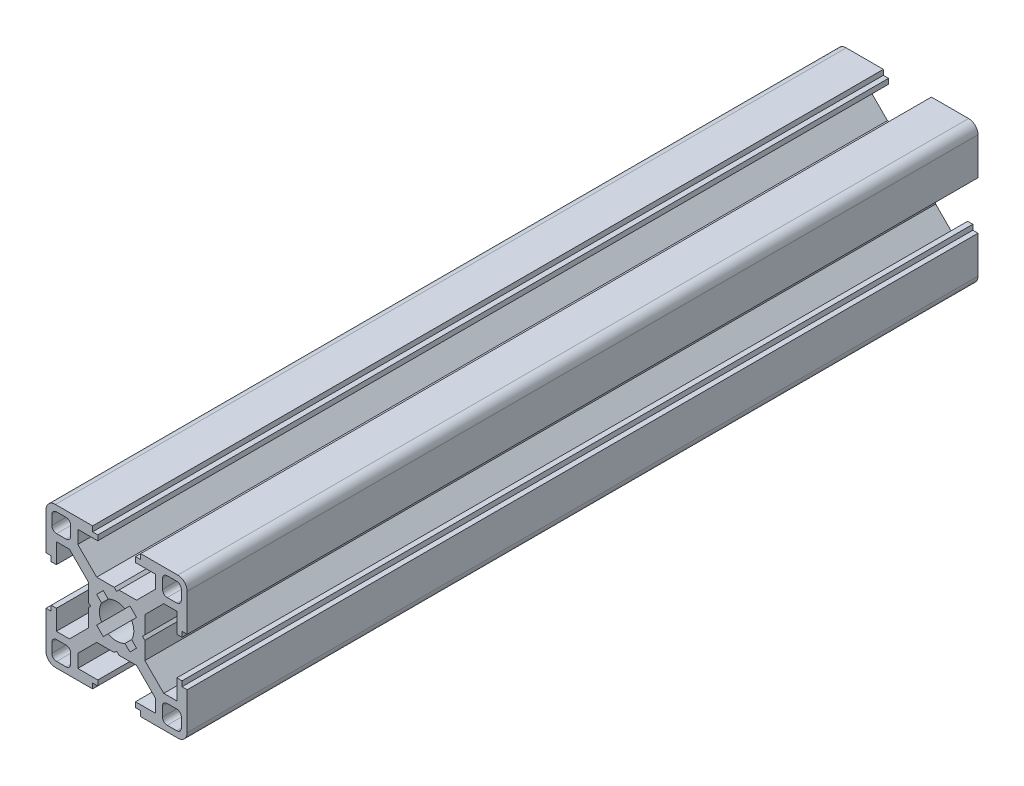
SolidWorks part; units mm, degrees
material "1060 Alloy"
ref_plane "Front Plane" through (0, 0, 0) normal (0, 0, 1) x (1, 0, 0)
ref_plane "Top Plane" through (0, 0, 0) normal (0, 1, 0) x (1, 0, 0)
ref_plane "Right Plane" through (0, 0, 0) normal (1, 0, 0) x (0, 0, -1)
sketch "Sketch1" plane through (0, 0, 0) normal (0, 0, 1) x (1, 0, 0)
  line L0 (5.1, 15) -> (13, 15)
  line L1 (15, -15) -> (-15, -15) construction
  line L2 (15, -15) -> (15, 15) construction
  line L3 (15, 15) -> (-15, 15) construction
  line L4 (-15, -15) -> (-15, 15) construction
  line L5 (15, -15) -> (-15, 15) construction
  line L6 (15, 15) -> (-15, -15) construction
  line L7 (-6, -6) -> (6, -6)
  line L8 (-6, -6) -> (-6, 6)
  line L9 (-6, 6) -> (4.2322, 6)
  line L10 (6, -6) -> (6, 4.2322)
  line L11 (-6, -6) -> (5.7915, 5.7915) construction
  line L12 (-6, 6) -> (6, -6) construction
  line L13 (15, 13) -> (15, 5.1)
  line L14 (15, 5.1) -> (13.9, 5.1)
  line L15 (13.9, 5.1) -> (13.9, 4)
  line L16 (13.9, 4) -> (12.8, 4)
  line L17 (12.8, 4) -> (12.8, 8.25)
  line L18 (12.8, 8.25) -> (10.0178, 8.25)
  line L19 (10.0178, 8.25) -> (6, 4.2322)
  line L20 (5.1, 15) -> (5.1, 13.9)
  line L21 (5.1, 13.9) -> (4, 13.9)
  line L22 (4, 13.9) -> (4, 12.8)
  line L23 (4, 12.8) -> (8.25, 12.8)
  line L24 (8.25, 12.8) -> (8.25, 10.0178)
  line L25 (8.25, 10.0178) -> (4.2322, 6)
  line L26 (4.2322, 6) -> (6, 4.2322) construction
  line L28 (13.75, 9.75) -> (9.75, 9.75)
  line L29 (13.75, 9.75) -> (13.75, 13.75)
  line L30 (13.75, 13.75) -> (9.75, 13.75)
  line L31 (9.75, 9.75) -> (9.75, 13.75)
  line L32 (13.75, 9.75) -> (9.75, 13.75) construction
  line L33 (13.75, 13.75) -> (9.75, 9.75) construction
  circle A0 centre (0, 0) radius 3.65
  arc A1 (15, 13) -> (13, 15) centre (13, 13) ccw
  point P12 (11.75, 11.75)
  dimension "D1" = 7.3
  dimension "D9" = 2
  dimension "D10" = 4
  dimension "D2" = 30
  dimension "D3" = 9
  dimension "D4" = 6.8
  dimension "D5" = 5.1
  dimension "D6" = 4
  dimension "D7" = 8.25
  dimension "D8" = 2.5
  dimension "D11" = 1.5
extrude "Boss-Extrude1" add sketch "Sketch1" along normal blind 168
fillet "Fillet1" radius 1 4 edges at (13.75, 9.75, 84) (13.75, 13.75, 84) (9.75, 13.75, 84) (9.75, 9.75, 84)
pattern_circular "CirPattern1" count 4 over 360 about axis through (0, 0, 0) along (0, 0, 1) of "Boss-Extrude1", "Fillet1"
sketch "Sketch2" plane through (0, 0, 0) normal (0, 0, -1) x (-1, 0, 0)
  line L0 (0, 5.5) -> (-0.5, 6)
  line L1 (-4.2322, 6) -> (4.2322, 6) construction
  line L2 (-0.5, 6) -> (0.5, 6)
  line L3 (0.5, 6) -> (0, 5.5)
  point P4 (0, 6)
  dimension "D1" = 0.5
extrude "Cut-Extrude1" cut sketch "Sketch2" against normal through all
sketch "Sketch3" plane through (0, 0, 0) normal (0, 0, -1) x (-1, 0, 0)
  line L0 (-1.7751, 3.1893) -> (-2.8284, 4.2426)
  line L1 (-2.8284, 4.2426) -> (-4.2426, 2.8284)
  line L2 (-4.2426, 2.8284) -> (-3.1893, 1.7751)
  line L3 (-3.5355, 3.5355) -> (0, 0) construction
  line L4 (-6, 4.2322) -> (-10.0178, 8.25) construction
  circle A0 centre (0, 0) radius 3.65 construction
  arc A1 (-3.1893, 1.7751) -> (-1.7751, 3.1893) centre (0, 0) cw
  dimension "D1" = 2
  dimension "D2" = 5
extrude "Cut-Extrude2" cut sketch "Sketch3" against normal through all
pattern_circular "CirPattern2" count 4 over 360 about axis through (0, 0, 0) along (0, 0, 1) of "Cut-Extrude1", "Cut-Extrude2"
